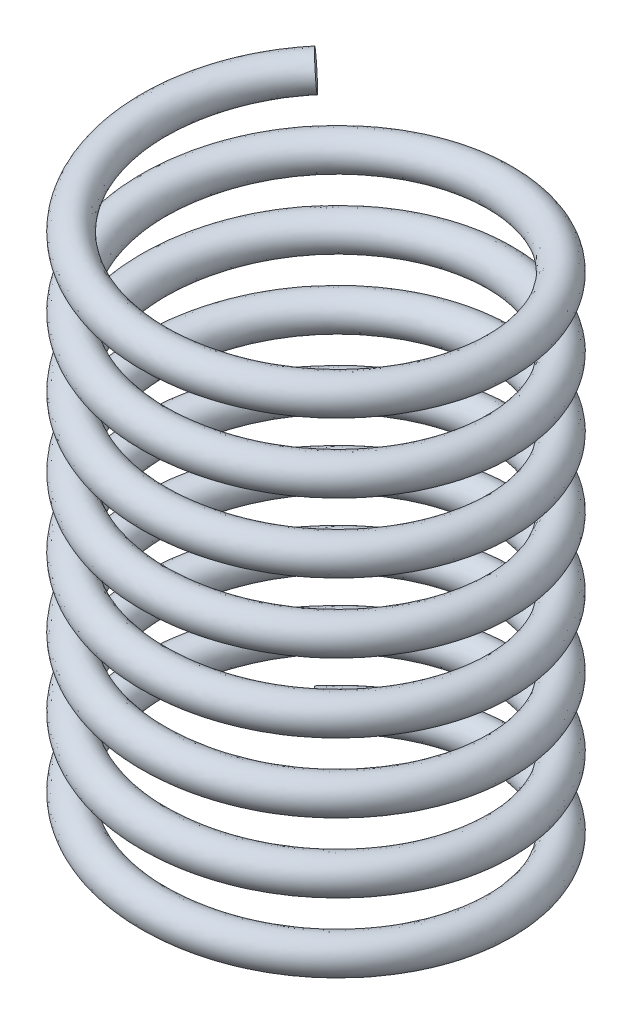
SolidWorks part; units mm, degrees
ref_plane "Front Plane" through (0, 0, 0) normal (0, 0, 1) x (1, 0, 0)
ref_plane "Top Plane" through (0, 0, 0) normal (0, 1, 0) x (1, 0, 0)
ref_plane "Right Plane" through (0, 0, 0) normal (1, 0, 0) x (0, 0, -1)
sketch "Sketch2" plane through (0, 0, 0) normal (0, 1, 0) x (1, 0, 0)
  circle A0 centre (0, 0) radius 2.5
  dimension "D1" = 5
curve "Helix/Spiral1" pitch 1 height 8 turns 8
sweep "Sweep1" add path "Helix/Spiral1" circular profile diameter 0.5 parameters "D3"=0.5
